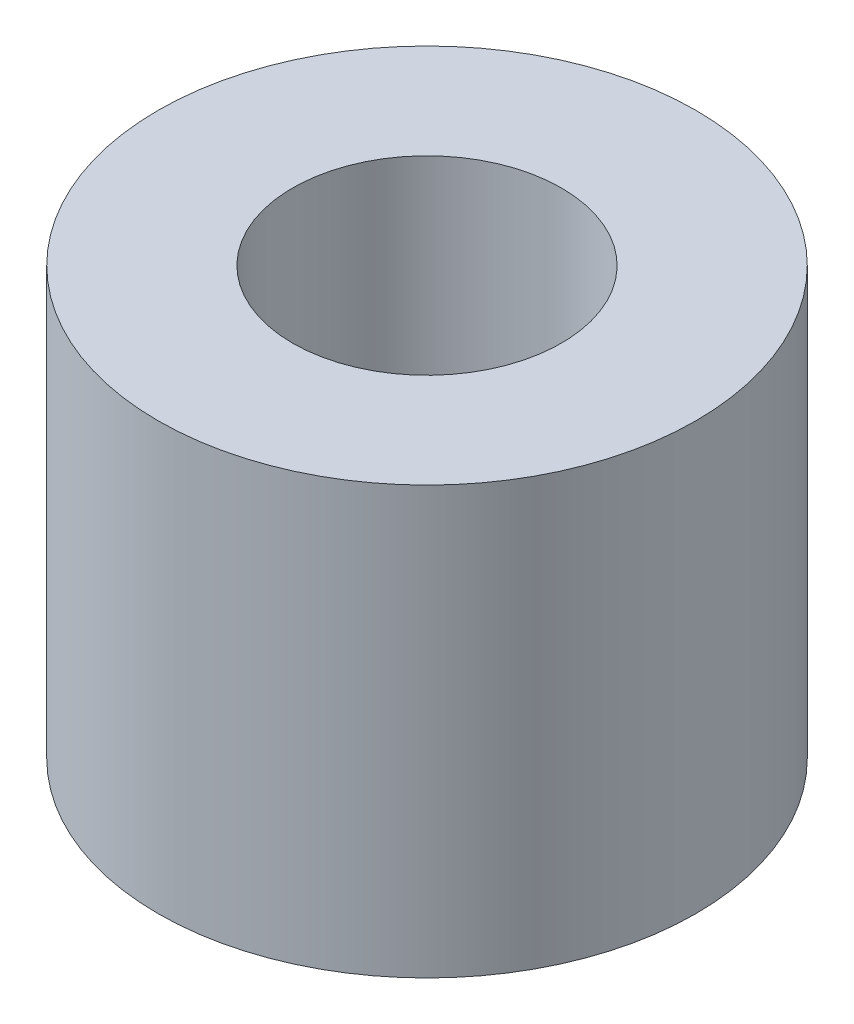
SolidWorks part; units mm, degrees
ref_plane "Front Plane" through (0, 0, 0) normal (0, 0, 1) x (1, 0, 0)
ref_plane "Top Plane" through (0, 0, 0) normal (0, 1, 0) x (1, 0, 0)
ref_plane "Right Plane" through (0, 0, 0) normal (1, 0, 0) x (0, 0, -1)
sketch "Sketch1" plane through (0, 0, 0) normal (0, 1, 0) x (1, 0, 0)
  circle A0 centre (0, 0) radius 2
  circle A1 centre (0, 0) radius 4
  dimension "D1" = 2
  dimension "D2" = 8
extrude "Boss-Extrude1" add sketch "Sketch1" along normal blind 6.35
